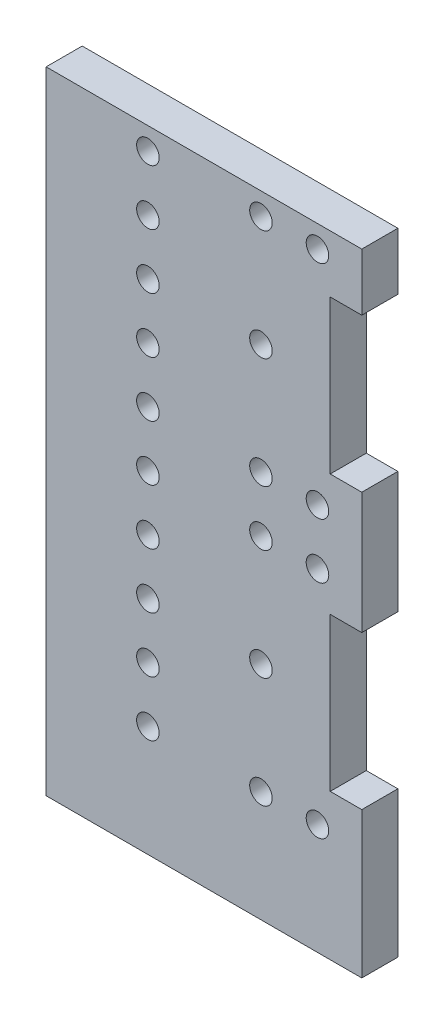
SolidWorks part; units mm, degrees
ref_plane "Front Plane" through (0, 0, 0) normal (0, 0, 1) x (1, 0, 0)
ref_plane "Top Plane" through (0, 0, 0) normal (0, 1, 0) x (1, 0, 0)
ref_plane "Right Plane" through (0, 0, 0) normal (1, 0, 0) x (0, 0, -1)
sketch "Sketch1" plane through (0, 0, 0) normal (0, 0, 1) x (1, 0, 0)
  line L0 (7, 11.46) -> (5.6, 11.46)
  line L1 (-7, 14) -> (7, 14)
  line L2 (-7, 14) -> (-7, -14)
  line L3 (-7, -14) -> (7, -14)
  line L4 (7, 14) -> (7, 11.46)
  line L5 (-7, 14) -> (7, -14) construction
  line L6 (-7, -14) -> (7, 14) construction
  line L7 (5.6, 11.46) -> (5.6, 4.66)
  line L8 (5.6, 4.66) -> (7, 4.66)
  line L9 (7, -0.732) -> (5.6, -0.732)
  line L10 (5.6, -0.732) -> (5.6, -7.532)
  line L11 (5.6, -7.532) -> (7, -7.532)
  line L12 (7, -7.532) -> (7, -14)
  line L13 (7, 4.66) -> (7, -0.732)
  point P0 (0, 0)
  dimension "D1" = 14
  dimension "D2" = 28
  dimension "D3" = 1.4
  dimension "D4" = 6.8
  dimension "D5" = 2.54
  dimension "D6" = 14.732
extrude "Boss-Extrude1" add sketch "Sketch1" along normal blind 1.6
sketch "Sketch2" plane through (0, 0, 1.6) normal (0, 0, 1) x (1, 0, 0)
  line L0 (5.0349, -6.627) -> (5.0349, -9.082) construction
  line L1 (5.0349, -9.082) -> (2.5276, -9.082) construction
  circle A0 centre (-2.4869, 13.0133) radius 0.5
  circle A1 centre (-2.4869, 10.5583) radius 0.5
  circle A2 centre (-2.4869, 8.1033) radius 0.5
  circle A3 centre (-2.4869, 5.6482) radius 0.5
  circle A4 centre (-2.4869, 3.1932) radius 0.5
  circle A5 centre (-2.4869, 0.7381) radius 0.5
  circle A6 centre (-2.4869, -1.7169) radius 0.5
  circle A7 centre (-2.4869, -6.627) radius 0.5
  circle A8 centre (-2.4869, -9.082) radius 0.5
  circle A9 centre (2.5276, -4.172) radius 0.5
  circle A10 centre (2.5276, 8.1033) radius 0.5
  circle A11 centre (-2.4869, -4.172) radius 0.5
  circle A12 centre (2.5276, 0.7381) radius 0.5
  circle A13 centre (2.5276, 3.1932) radius 0.5
  circle A14 centre (5.0349, 3.1932) radius 0.5
  circle A15 centre (5.0349, 0.7381) radius 0.5
  circle A16 centre (2.5276, 13.0133) radius 0.5
  circle A17 centre (5.0349, 13.0133) radius 0.5
  circle A18 centre (5.0349, -9.082) radius 0.5
  circle A19 centre (2.5276, -9.082) radius 0.5
  point P0 (-2.4869, -9.082)
  point P1 (0.0204, -9.082)
  point P4 (2.5276, -9.082)
  point P5 (5.0349, -9.082)
  point P6 (0.0204, -6.627)
  point P7 (2.5276, -6.627)
  point P8 (5.0349, -6.627)
  point P9 (0.0204, -4.172)
  point P10 (2.5276, -4.172)
  point P11 (5.0349, -4.172)
  point P12 (0.0204, -1.7169)
  point P13 (2.5276, -1.7169)
  point P14 (5.0349, -1.7169)
  point P15 (0.0204, 0.7381)
  point P16 (2.5276, 0.7381)
  point P17 (5.0349, 0.7381)
  point P18 (0.0204, 3.1932)
  point P19 (2.5276, 3.1932)
  point P20 (5.0349, 3.1932)
  point P21 (0.0204, 5.6482)
  point P22 (2.5276, 5.6482)
  point P23 (5.0349, 5.6482)
  point P24 (0.0204, 8.1033)
  point P25 (2.5276, 8.1033)
  point P26 (5.0349, 8.1033)
  point P27 (0.0204, 10.5583)
  point P28 (2.5276, 10.5583)
  point P29 (5.0349, 10.5583)
  point P30 (0.0204, 13.0133)
  point P31 (2.5276, 13.0133)
  point P32 (5.0349, 13.0133)
  point P33 (-2.4869, -6.627)
  point P34 (-2.4869, -4.172)
  point P35 (-2.4869, -1.7169)
  point P36 (-2.4869, 0.7381)
  point P37 (-2.4869, 3.1932)
  point P38 (-2.4869, 5.6482)
  point P39 (-2.4869, 8.1033)
  point P40 (-2.4869, 10.5583)
  point P41 (-2.4869, 13.0133)
  dimension "D3" = 1
  dimension "D1" = 4
  dimension "D2" = 10
extrude "Cut-Extrude1" cut sketch "Sketch2" against normal through all
